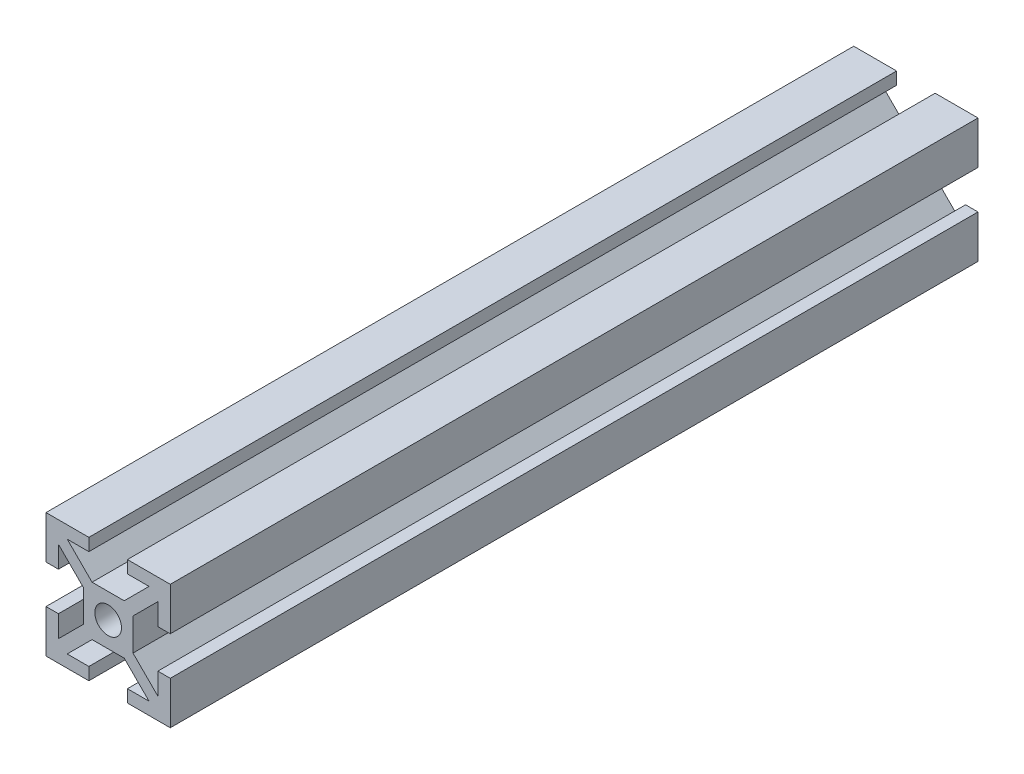
SolidWorks part; units mm, degrees
ref_plane "Plan de face" through (0, 0, 0) normal (0, 0, 1) x (1, 0, 0)
ref_plane "Plan de dessus" through (0, 0, 0) normal (0, 1, 0) x (1, 0, 0)
ref_plane "Plan de droite" through (0, 0, 0) normal (1, 0, 0) x (0, 0, -1)
sketch "Esquisse1" plane through (0, 0, 0) normal (0, 0, 1) x (1, 0, 0)
  line L0 (20, 13.1) -> (18, 13.1)
  line L1 (0, 0) -> (6.9, 0)
  line L2 (0, 0) -> (0, 6.9)
  line L3 (0, 20) -> (6.9, 20)
  line L4 (20, 0) -> (20, 6.9)
  line L5 (18, 13.1) -> (18, 16.5858)
  line L6 (0, 0) -> (20, 20) construction
  line L7 (14, 12.5858) -> (14, 10)
  line L8 (14, 12.5858) -> (18, 16.5858)
  line L9 (13.1, 20) -> (13.1, 18)
  line L10 (13.1, 18) -> (16.5858, 18)
  line L11 (12.5858, 14) -> (16.5858, 18)
  line L12 (12.5858, 14) -> (10, 14)
  line L13 (14, 7.4142) -> (14, 10)
  line L14 (14, 7.4142) -> (18, 3.4142)
  line L15 (18, 6.9) -> (18, 3.4142)
  line L16 (20, 6.9) -> (18, 6.9)
  line L17 (13.1, 2) -> (16.5858, 2)
  line L18 (12.5858, 6) -> (16.5858, 2)
  line L19 (13.1, 0) -> (13.1, 2)
  line L20 (12.5858, 6) -> (10, 6)
  line L21 (7.4142, 6) -> (10, 6)
  line L22 (7.4142, 6) -> (3.4142, 2)
  line L23 (6.9, 2) -> (3.4142, 2)
  line L24 (6.9, 0) -> (6.9, 2)
  line L25 (2, 6.9) -> (2, 3.4142)
  line L26 (6, 7.4142) -> (2, 3.4142)
  line L27 (0, 6.9) -> (2, 6.9)
  line L28 (6, 7.4142) -> (6, 10)
  line L29 (6, 12.5858) -> (6, 10)
  line L30 (6, 12.5858) -> (2, 16.5858)
  line L31 (2, 13.1) -> (2, 16.5858)
  line L32 (0, 13.1) -> (2, 13.1)
  line L33 (6.9, 18) -> (3.4142, 18)
  line L34 (7.4142, 14) -> (3.4142, 18)
  line L35 (6.9, 20) -> (6.9, 18)
  line L36 (7.4142, 14) -> (10, 14)
  line L37 (20, 13.1) -> (20, 20)
  line L38 (13.1, 20) -> (20, 20)
  line L39 (0, 13.1) -> (0, 20)
  line L40 (13.1, 0) -> (20, 0)
  circle A0 centre (10, 10) radius 2.15
  point P51 (10, 10)
  dimension "D2" = 4.3
  dimension "D1" = 20
  dimension "D3" = 2
  dimension "D4" = 6.2
  dimension "D5" = 6
  dimension "D6" = 2
  dimension "D7" = 4
extrude "Boss.-Extru.1" add sketch "Esquisse1" along normal blind 130
